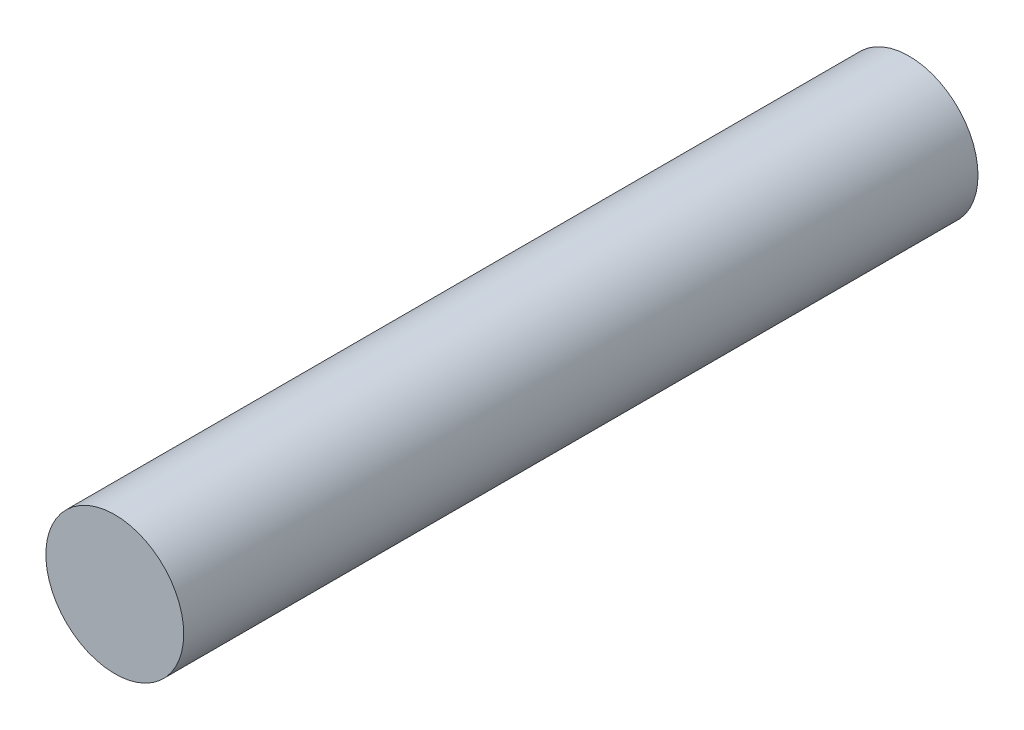
SolidWorks part; units mm, degrees
material "AISI 304"
ref_plane "Front Plane" through (0, 0, 0) normal (0, 0, 1) x (1, 0, 0)
ref_plane "Top Plane" through (0, 0, 0) normal (0, 1, 0) x (1, 0, 0)
ref_plane "Right Plane" through (0, 0, 0) normal (1, 0, 0) x (0, 0, -1)
sketch "Sketch1" plane through (0, 0, 0) normal (0, 0, 1) x (1, 0, 0)
  circle A0 centre (0, 0) radius 4
  dimension "D1" = 8
extrude "Boss-Extrude2" add sketch "Sketch1" along normal blind 46.1
